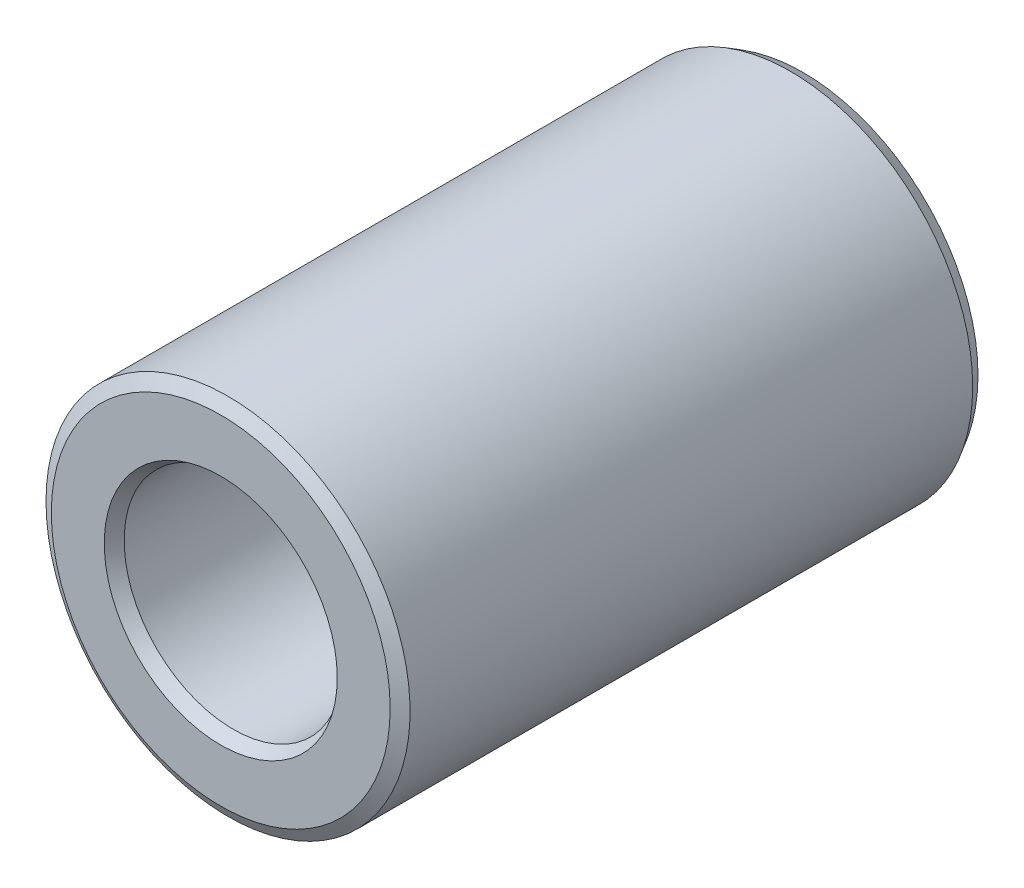
SolidWorks part; units mm, degrees
ref_plane "Front Plane" through (0, 0, 0) normal (0, 0, 1) x (1, 0, 0)
ref_plane "Top Plane" through (0, 0, 0) normal (0, 1, 0) x (1, 0, 0)
ref_plane "Right Plane" through (0, 0, 0) normal (1, 0, 0) x (0, 0, -1)
sketch "Sketch1" plane through (0, 0, 0) normal (0, 0, 1) x (1, 0, 0)
  circle A0 centre (0, 0) radius 2.5
  circle A1 centre (0, 0) radius 1.5
  dimension "D1" = 5
  dimension "D2" = 3
extrude "Boss-Extrude1" add sketch "Sketch1" along normal mid plane 8
chamfer "Chamfer1" distance 0.1 angle 60 4 edges at (1.5, 0, -4) (2.5, 0, -4) (1.5, 0, 4) (2.5, 0, 4)
